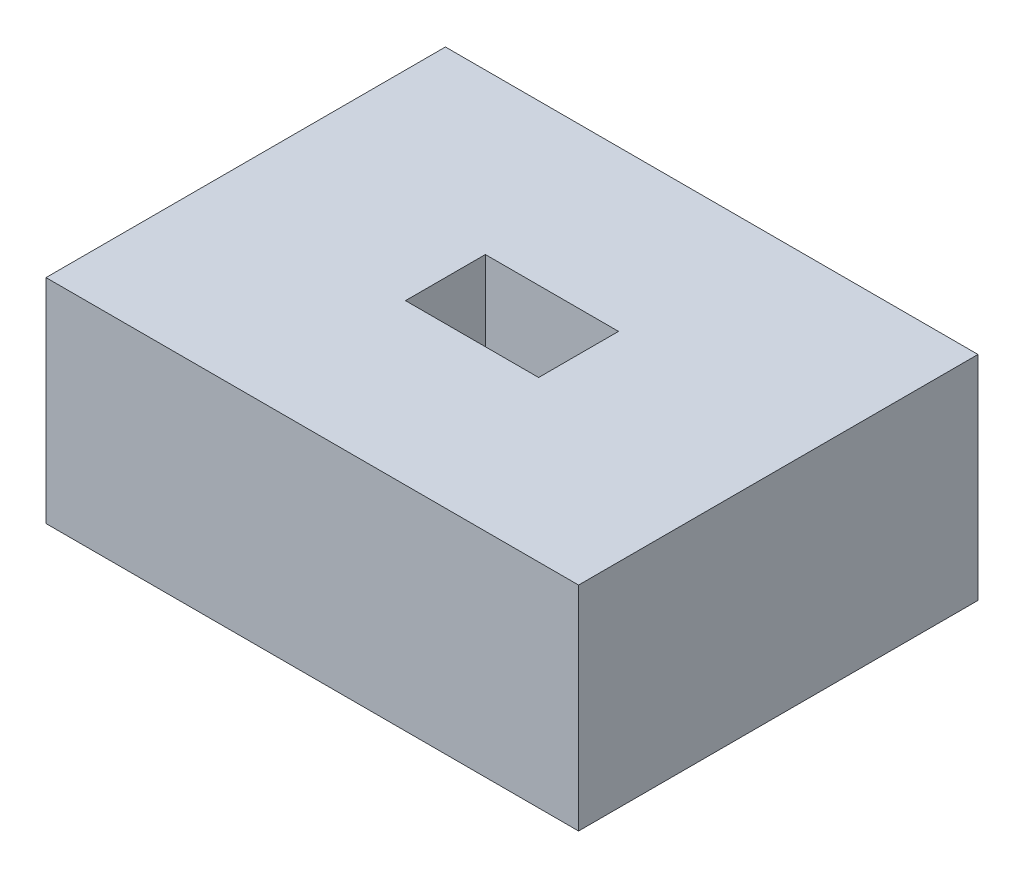
SolidWorks part; units mm, degrees
ref_plane "Front" through (0, 0, 0) normal (0, 0, 1) x (1, 0, 0)
ref_plane "Top" through (0, 0, 0) normal (0, 1, 0) x (1, 0, 0)
ref_plane "Right" through (0, 0, 0) normal (1, 0, 0) x (0, 0, -1)
sketch "Sketch1" plane through (0, 0, 0) normal (0, 1, 0) x (1, 0, 0)
  line L5 (-10, -7.5) -> (10, -7.5)
  line L6 (-10, -7.5) -> (-10, 7.5)
  line L11 (-10, 7.5) -> (10, 7.5)
  line L12 (10, -7.5) -> (10, 7.5)
  line L13 (-10, -7.5) -> (10, 7.5) construction
  line L14 (-10, 7.5) -> (10, -7.5) construction
  point P0 (0, 0)
  dimension "D1" = 15
  dimension "D2" = 20
extrude "Boss-Extrude1" add sketch "Sketch1" along normal blind 8
sketch "Sketch2" plane through (0, 8, 0) normal (0, 1, 0) x (1, 0, 0)
  line L1 (-2.5, -1.5) -> (2.5, -1.5)
  line L2 (-2.5, -1.5) -> (-2.5, 1.5)
  line L3 (-2.5, 1.5) -> (2.5, 1.5)
  line L4 (2.5, -1.5) -> (2.5, 1.5)
  line L5 (-2.5, -1.5) -> (2.5, 1.5) construction
  line L6 (-2.5, 1.5) -> (2.5, -1.5) construction
  point P0 (0, 0)
  point P5 (5.4774, 0)
  point P6 (0, 0)
  dimension "D1" = 3
  dimension "D2" = 5
extrude "Cut-Extrude1" cut sketch "Sketch2" against normal blind 3.2
sketch "Sketch3" plane through (0, 0, 0) normal (0, -1, 0) x (1, 0, 0)
  line L8 (2.5, -1.5) -> (2.5, 1.5)
  line L9 (-2.5, -1.5) -> (2.5, -1.5)
  line L10 (-2.5, 1.5) -> (-2.5, -1.5)
  line L11 (2.5, 1.5) -> (-2.5, 1.5)
  line L12 (2.5, -1.5) -> (2.5, 1.5)
  line L13 (-2.5, -1.5) -> (2.5, -1.5)
  line L14 (-2.5, 1.5) -> (-2.5, -1.5)
  line L15 (2.5, 1.5) -> (-2.5, 1.5)
  dimension "D1" = 0
extrude "Boss-Extrude2" add sketch "Sketch3" along normal blind 3
